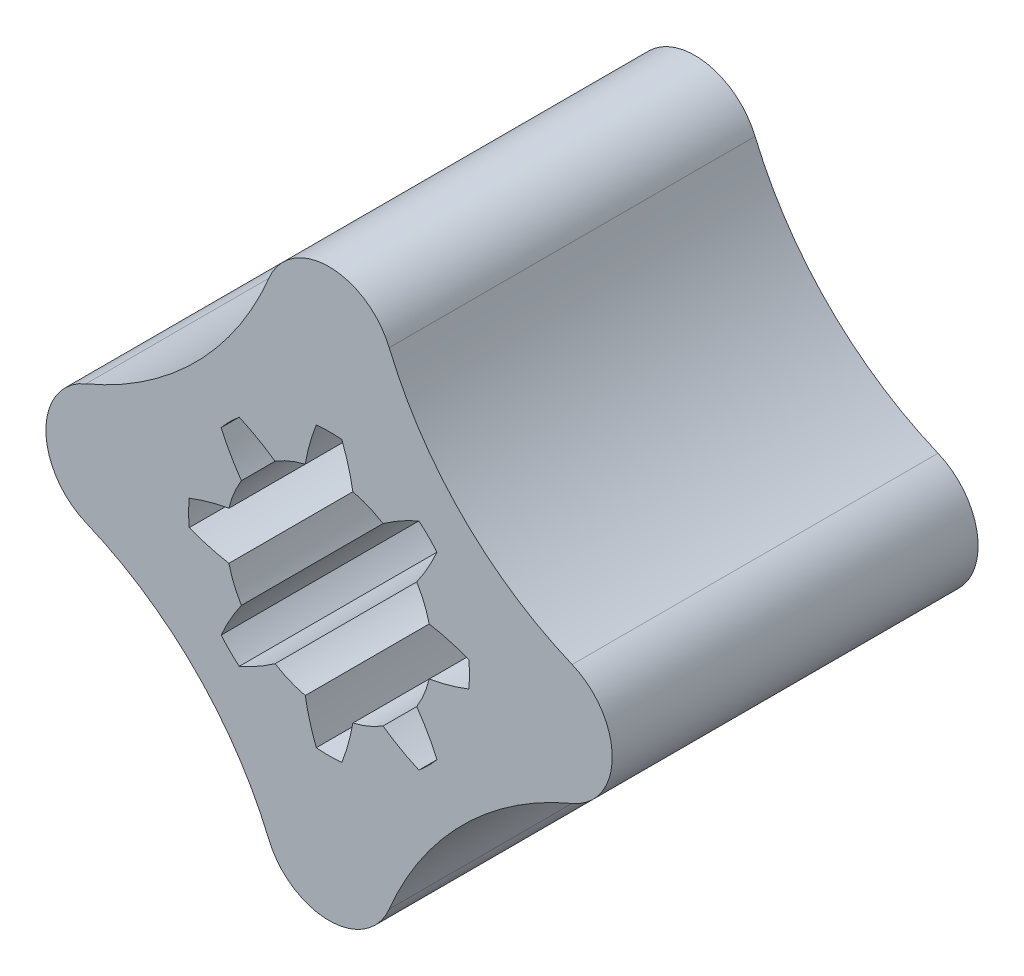
SolidWorks part; units mm, degrees
material "AISI 4140"
ref_plane "Front Plane" through (0, 0, 0) normal (0, 0, 1) x (1, 0, 0)
ref_plane "Top Plane" through (0, 0, 0) normal (0, 1, 0) x (1, 0, 0)
ref_plane "Right Plane" through (0, 0, 0) normal (1, 0, 0) x (0, 0, -1)
sketch "Sketch1" plane through (0, 0, 0) normal (0, 0, 1) x (1, 0, 0)
  line L0 (0, 0) -> (0, 30.3913) construction
  line L1 (0, 0) -> (36.2247, 0) construction
  line L2 (0, 0) -> (30.7829, 0) construction
  line L3 (0, 0) -> (21.991, 21.991) construction
  circle A0 centre (0, 0) radius 16.64 construction
  circle A1 centre (0, 0) radius 11.1 construction
  circle A2 centre (0, 0) radius 6
  arc A3 (3.5352, 14.2851) -> (-3.5352, 14.2851) centre (0, 12.8091) ccw
  arc A4 (14.2851, -3.5352) -> (14.2851, 3.5352) centre (12.8091, 0) ccw
  arc A6 (3.5352, -14.2851) -> (-3.5352, -14.2851) centre (0, -12.8091) cw
  arc A7 (-14.2851, -3.5352) -> (-14.2851, 3.5352) centre (-12.8091, 0) cw
  arc A9 (3.5352, 14.2851) -> (14.2851, 3.5352) centre (21.991, 21.991) ccw
  arc A10 (-3.5352, 14.2851) -> (-14.2851, 3.5352) centre (-21.991, 21.991) cw
  arc A13 (-3.5352, -14.2851) -> (-14.2851, -3.5352) centre (-21.991, -21.991) ccw
  arc A14 (3.5352, -14.2851) -> (14.2851, -3.5352) centre (21.991, -21.991) cw
  dimension "D1" = 22.2
  dimension "D2" = 33.28
  dimension "D3" = 12
  dimension "D6" = 20
  dimension "D7" = 3.8309
  dimension "D4" = 90
  dimension "D5" = 45
extrude "Extrude1" add sketch "Sketch1" along normal blind 21.5
sketch "Sketch4" plane through (0, 0, 0) normal (1, 0, 0) x (0, 0, -1)
  line L0 (0, 0) -> (-35.6112, 0) construction
  line L1 (-21.5, 14.2851) -> (-21.5, 3.5352) construction
  line L3 (0, 0) -> (-21.5, 0)
  line L4 (-7.2, 6.05) -> (-21.5, 6.05)
  line L5 (-5, 8.25) -> (0, 8.25)
  line L6 (-21.5, 6.05) -> (-21.5, 0)
  line L7 (0, 3.5352) -> (0, 14.2851) construction
  line L9 (0, 8.25) -> (0, 0)
  line L10 (-7.2, 6.05) -> (-5, 8.25)
  line L11 (-21.5, 3.5352) -> (-21.5, -3.5352) construction
  dimension "D1" = 16.5
  dimension "D2" = 5
  dimension "D3" = 45
  dimension "D4" = 12.1
revolve "Cut-Revolve1" cut sketch "Sketch4" angle 360 about L0
sketch "Sketch2" plane through (0, 0, 0) normal (0, 0, -1) x (-1, 0, 0)
  line L0 (0, 0) -> (32.9156, 0) construction
  line L1 (0, 0) -> (0, 28.3412) construction
  arc A0 (0.75, 8.2158) -> (-0.75, 8.2158) centre (0, 0) ccw
  arc A1 (-0.75, 8.2158) -> (-1.4, 5.8858) centre (10.4622, 3.8323) ccw
  arc A3 (0.75, 8.2158) -> (1.4, 5.8858) centre (-10.4622, 3.8323) cw
  arc A4 (1.4, 5.8858) -> (-1.4, 5.8858) centre (0, 0) ccw
  circle A7 centre (0, 0) radius 6.05 construction
  dimension "D1" = 16.5
  dimension "D4" = 12.0386
  dimension "D2" = 1.5
  dimension "D3" = 2.8
extrude "Extrude2" cut sketch "Sketch2" against normal up to next
pattern_circular "CirPattern1" count 8 over 360 about axis through (0, 0, 0) along (0, 0, 1) of "Extrude2"
